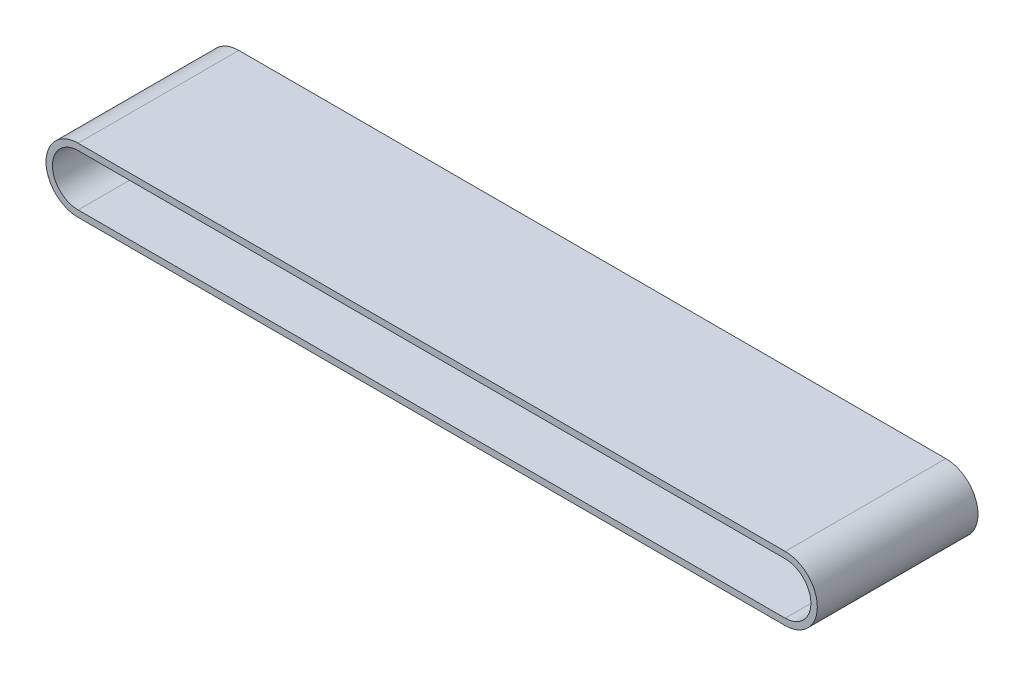
SolidWorks part; units mm, degrees
ref_plane "Front Plane" through (0, 0, 0) normal (0, 0, 1) x (1, 0, 0)
ref_plane "Top Plane" through (0, 0, 0) normal (0, 1, 0) x (1, 0, 0)
ref_plane "Right Plane" through (0, 0, 0) normal (1, 0, 0) x (0, 0, -1)
sketch "Sketch2" plane through (0, 0, 0) normal (0, 0, 1) x (1, 0, 0)
  line L1 (0, 0) -> (-1100, 0)
  line L2 (0, 0) -> (0, 100)
  line L3 (0, 100) -> (-1100, 100)
  line L4 (-1100, 0) -> (-1100, 100)
  circle A0 centre (-1100, 50) radius 50
  circle A1 centre (0, 50) radius 50
  dimension "D3" = 100
  dimension "D4" = 100
  dimension "D1" = 1100
  dimension "D2" = 100
extrude "Boss-Extrude1" add sketch "Sketch2" along normal blind 250 contours A0 | L2 L1 L4 L3 | A1
sketch "Sketch3" plane through (0, 0, 250) normal (0, 0, 1) x (1, 0, 0)
  line L0 (0, 100) -> (-1100, 100) construction
  line L1 (-1100, 90) -> (0, 90)
  line L2 (-1100, 90) -> (-1100, 10)
  line L3 (-1100, 10) -> (0, 10)
  line L4 (0, 90) -> (0, 10)
  circle A0 centre (-1100, 50) radius 40
  circle A1 centre (0, 50) radius 40
  arc A2 (-1100, 100) -> (-1100, 0) centre (-1100, 50) ccw construction
  dimension "D4" = 10
  dimension "D1" = 1100
  dimension "D2" = 80
  dimension "D3" = 10
extrude "Cut-Extrude1" cut sketch "Sketch3" against normal through all contours A1 | L2 L1 L4 L3 | A0
ref_plane "Plane1" through (0, 100, 0) normal (0, 0, -1) x (-1, 0, 0)
